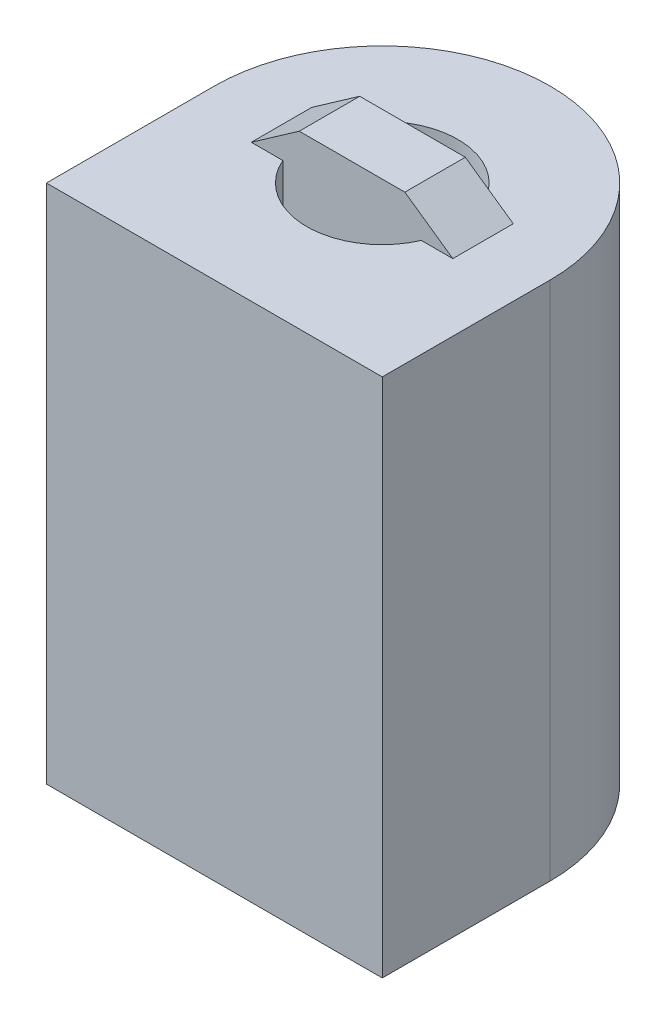
SolidWorks part; units mm, degrees
ref_plane "Front Plane" through (0, 0, 0) normal (0, 0, 1) x (1, 0, 0)
ref_plane "Top Plane" through (0, 0, 0) normal (0, 1, 0) x (1, 0, 0)
ref_plane "Right Plane" through (0, 0, 0) normal (1, 0, 0) x (0, 0, -1)
sketch "Sketch1" plane through (0, 0, 0) normal (0, 1, 0) x (1, 0, 0)
  circle A0 centre (0, 0) radius 12.7
  dimension "D1" = 25.4
extrude "Boss-Extrude1" add sketch "Sketch1" along normal blind 38.1
sketch "Sketch2" plane through (0, 38.1, 0) normal (0, 1, 0) x (1, 0, 0)
  circle A0 centre (0, 0) radius 5.715
  dimension "D1" = 11.43
extrude "Cut-Extrude1" cut sketch "Sketch2" against normal through all
sketch "Sketch3" plane through (0, 0, 0) normal (0, -1, 0) x (1, 0, 0)
  circle A0 centre (0, 0) radius 9.3345
  dimension "D1" = 18.669
extrude "Cut-Extrude2" cut sketch "Sketch3" against normal blind 12.7
sketch "Sketch4" plane through (0, 38.1, 0) normal (0, 1, 0) x (1, 0, 0)
  circle A0 centre (0, 0) radius 5.715 construction
  circle A1 centre (0, 0) radius 12.7
  circle A2 centre (0, 0) radius 12.7
  circle A3 centre (0, 0) radius 5.715
  dimension "D1" = 0
extrude "Boss-Extrude2" add sketch "Sketch4" along normal blind 1.27
sketch "Sketch5" plane through (0, 39.37, 0) normal (0, 1, 0) x (1, 0, 0)
  line L1 (5.715, 2.286) -> (-5.715, 2.286)
  line L2 (5.715, 2.286) -> (5.715, -2.286)
  line L3 (5.715, -2.286) -> (-5.715, -2.286)
  line L4 (-5.715, 2.286) -> (-5.715, -2.286)
  line L5 (5.715, 2.286) -> (-5.715, -2.286) construction
  line L6 (5.715, -2.286) -> (-5.715, 2.286) construction
  circle A0 centre (0, 0) radius 5.715 construction
  point P0 (0, 0)
  dimension "D1" = 4.318
extrude "Boss-Extrude3" add sketch "Sketch5" against normal blind 6.35
sketch "Sketch6" plane through (0, 0, -2.286) normal (0, 0, -1) x (-1, 0, 0)
  line L1 (12.7, 39.37) -> (-12.7, 39.37) construction
  line L3 (7.62, 39.37) -> (-7.62, 39.37)
  line L4 (0, 44.45) -> (0, 0) construction
  line L5 (5.2379, 39.37) -> (5.2379, 40.9581) construction
  line L6 (-7.62, 39.37) -> (-3.9925, 41.91)
  line L7 (-3.9925, 41.91) -> (3.9925, 41.91)
  line L8 (3.9925, 41.91) -> (7.62, 39.37)
  dimension "D1" = 35
  dimension "D2" = 15.24
  dimension "D3" = 1.5881
  dimension "D4" = 2.54
extrude "Boss-Extrude4" add sketch "Sketch6" against normal up to surface (4.572 mm away) up to face at (0, 36.195, 2.286)
sketch "Sketch7" plane through (0, 39.37, 0) normal (0, 1, 0) x (1, 0, 0)
  line L0 (-12.7, 0) -> (-12.7, -12.7)
  line L1 (-12.7, -12.7) -> (12.7, -12.7)
  line L2 (12.7, -12.7) -> (12.7, 0)
  circle A0 centre (0, 0) radius 12.7 construction
  arc A1 (12.7, 0) -> (-12.7, 0) centre (0, 0) cw
  circle M1 centre (0, 0) radius 12.7
extrude "Boss-Extrude5" add sketch "Sketch7" against normal up to surface (39.37 mm away) contours L1 L2 M1 | L0 L1 M1 up to face at (0, 0, -9.3345)
